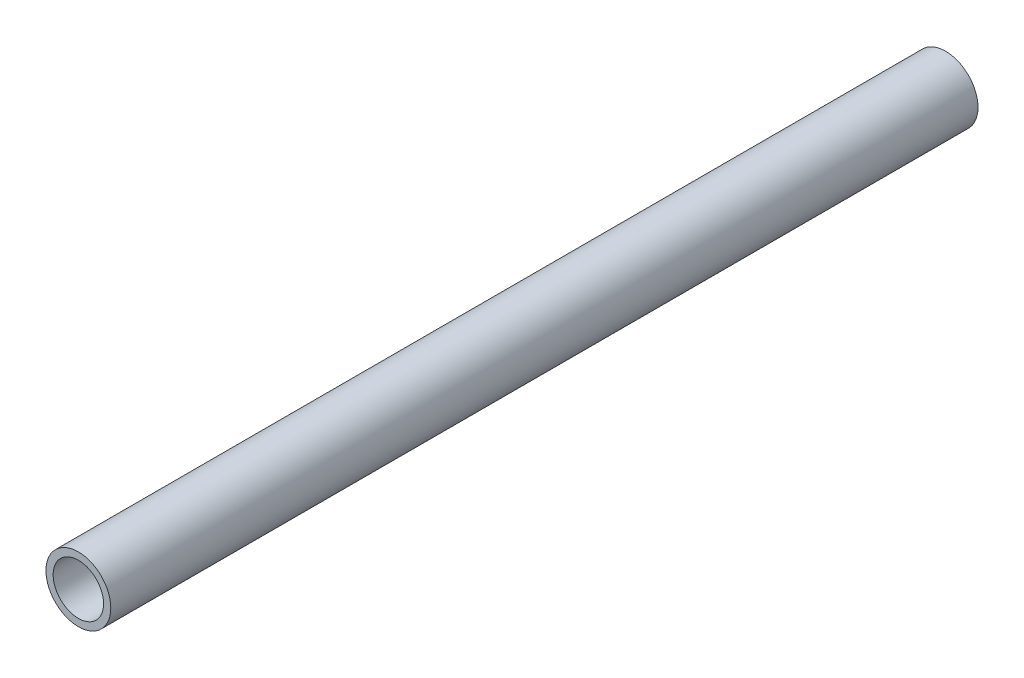
SolidWorks part; units mm, degrees
ref_plane "Front Plane" through (0, 0, 0) normal (0, 0, 1) x (1, 0, 0)
ref_plane "Top Plane" through (0, 0, 0) normal (0, 1, 0) x (1, 0, 0)
ref_plane "Right Plane" through (0, 0, 0) normal (1, 0, 0) x (0, 0, -1)
sketch "Sketch1" plane through (0, 0, 0) normal (0, 0, 1) x (1, 0, 0)
  circle A0 centre (0, 0) radius 7
  circle A1 centre (0, 0) radius 9
  dimension "D1" = 14
  dimension "D2" = 18
extrude "Boss-Extrude1" add sketch "Sketch1" along normal blind 240.71
